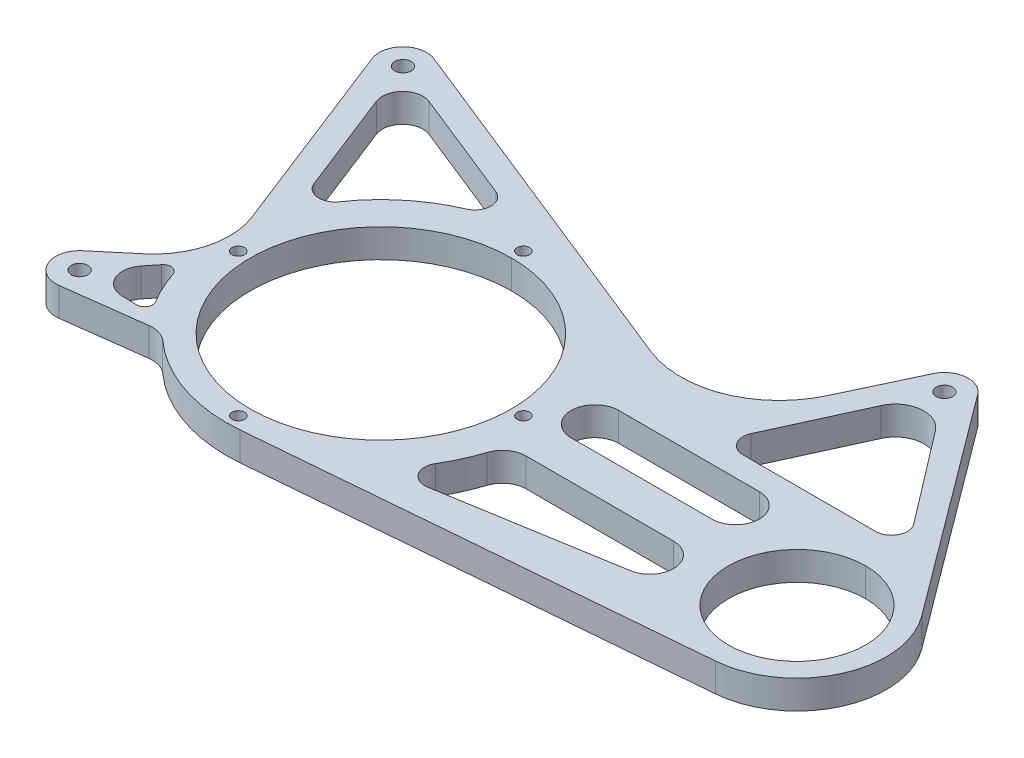
SolidWorks part; units mm, degrees
material "7075-T6 (SN)"
ref_plane "X-Y Datum" through (0, 0, 0) normal (0, 0, 1) x (1, 0, 0)
ref_plane "X-Z Datum" through (0, 0, 0) normal (0, 1, 0) x (1, 0, 0)
ref_plane "Y-Z Datum" through (0, 0, 0) normal (1, 0, 0) x (0, 0, -1)
sketch "Sketch1" plane through (0, 0, 0) normal (0, 1, 0) x (1, 0, 0)
  line L0 (-228.6, -165.1) -> (-123.19, -116.0015) construction
  line L1 (0, 0) -> (54.61, -127) construction
  line L2 (-123.19, -116.0015) -> (54.61, -127) construction
  line L3 (-228.6, -165.1) -> (-228.6, 0) construction
  line L4 (-116.84, 0) -> (0, 0) construction
  line L5 (-228.6, 0) -> (-116.84, 0) construction
  line L10 (-228.6, 0) -> (-123.19, -116.0015) construction
  line L11 (-123.19, -116.0015) -> (10.0337, -23.3342) construction
  line L15 (-207.9749, -9.9568) -> (-62.7807, -68.145)
  line L16 (-117.8957, -177.6872) -> (57.6671, -162.619)
  line L17 (17.67, -17.641) -> (83.2712, -105.6318)
  line L18 (1.4126, -19.2843) -> (-12.1766, -48.2122)
  line L20 (-211.7072, -147.0868) -> (-198.1514, -135.6819)
  line L21 (-220.3888, -22.2676) -> (-189.4301, -101.4224)
  line L22 (-172.4434, -159.7008) -> (-204.3552, -163.8219)
  circle A0 centre (-211.5182, -18.7982) radius 9.525 construction
  circle A2 centre (10.0337, -23.3342) radius 9.525 construction
  circle A3 centre (-211.5182, -18.7982) radius 3.3 construction
  circle A4 centre (-205.5752, -154.3754) radius 3.3 construction
  circle A5 centre (-123.19, -116.0015) radius 52.3875
  circle A6 centre (54.61, -127) radius 27.5
  circle A7 centre (0, 0) radius 12.7 construction
  circle A8 centre (-228.6, -165.1) radius 12.7 construction
  circle A9 centre (-228.6, 0) radius 12.7 construction
  circle A10 centre (10.0337, -23.3342) radius 3.3 construction
  circle A11 centre (-123.19, -173.1515) radius 2.5 construction
  circle A14 centre (-123.19, -116.0015) radius 61.9125 construction
  circle A15 centre (-123.19, -116.0015) radius 57.15 construction
  circle A17 centre (-205.5752, -154.3754) radius 9.525 construction
  circle A18 centre (54.61, -127) radius 35.75 construction
  circle A19 centre (-48.0406, -31.3647) radius 39.624 construction
  arc A20 (-12.1766, -48.2122) -> (-62.7807, -68.145) centre (-48.0406, -31.3647) cw
  arc A24 (57.6671, -162.619) -> (83.2712, -105.6318) centre (54.61, -127) ccw
  arc A25 (1.4126, -19.2843) -> (17.67, -17.641) centre (10.0337, -23.3342) cw
  circle A27 centre (-217.6792, -112.471) radius 30.3329 construction
  arc A29 (-198.1514, -135.6819) -> (-189.4301, -101.4224) centre (-217.6792, -112.471) ccw
  arc A30 (-220.3888, -22.2676) -> (-207.9749, -9.9568) centre (-211.5182, -18.7982) cw
  arc A31 (-164.4265, -162.1827) -> (-117.8957, -177.6872) centre (-123.19, -116.0015) ccw
  circle A32 centre (-171.1504, -169.7128) radius 10.0952 construction
  arc A33 (-204.3552, -163.8219) -> (-211.7072, -147.0868) centre (-205.5752, -154.3754) cw
  arc A34 (-172.4434, -159.7008) -> (-164.4265, -162.1827) centre (-171.1504, -169.7128) cw
  point P36 (-123.19, -116.0015)
  dimension "D1" = 165.1
  dimension "D2" = 105.41
  dimension "D8" = 25.4
  dimension "D9" = 104.775
  dimension "D10" = 55
  dimension "D11" = 19.05
  dimension "D12" = 6.6
  dimension "D23" = 5
  dimension "D14" = 123.825
  dimension "D19" = 79.248
  dimension "D20" = 31.3647
  dimension "D16" = 71.5
  dimension "D25" = 20.1904
  dimension "D21" = 20.9
  dimension "D26" = 60.6657
  dimension "D3" = 111.76
  dimension "D4" = 228.6
  dimension "D5" = 127
  dimension "D6" = 49.0985
  dimension "D7" = 283.21
  dimension "D13" = 25.4
  dimension "D15" = 25.4
  dimension "D17" = 25.4
  dimension "D18" = 48.0406
  dimension "D22" = 34.4248
  dimension "D24" = 57.15
  dimension "D27" = 10.9208
extrude "Boss-Extrude1" add sketch "Sketch1" along normal blind 11.43
hole_wizard "M6 Clearance Hole1" positions "Sketch2" profile "Sketch3" hole size "M6" standard "ANSI Metric" end condition through all
sketch "Sketch2" plane through (0, 0, 0) normal (0, -1, 0) x (-1, 0, 0)
  point P0 (-10.0337, -23.3342)
  point P3 (211.5182, -18.7982)
  point P6 (205.5752, -154.3754)
sketch "Sketch3" plane through (10.0337, 0, 23.3342) normal (1, 0, 0) x (0, 0, -1)
  line L0 (0, 0) -> (0, 11.43)
  line L1 (0, 11.43) -> (3.3, 11.43)
  line L2 (3.3, 11.43) -> (3.3, 0)
  line L5 (3.3, 0) -> (0, 0)
  line L11 (0, -6.35) -> (0, 107.95) construction
  dimension "Thru Hole Dia." = 6.6
  dimension "Thru Hole Depth" = 11.43
hole_wizard "Ø5.0mm Dowel Hole1" positions "Sketch4" profile "Sketch5" hole size "Ø5.0" standard "ANSI Metric" end condition through all
sketch "Sketch4" plane through (0, 0, 0) normal (0, -1, 0) x (-1, 0, 0)
  point P0 (123.19, -173.1515)
sketch "Sketch5" plane through (-123.19, 0, 173.1515) normal (1, 0, 0) x (0, 0, -1)
  line L0 (0, 0) -> (0, 11.43)
  line L1 (0, 11.43) -> (2.5, 11.43)
  line L2 (2.5, 11.43) -> (2.5, 0)
  line L5 (2.5, 0) -> (0, 0)
  line L11 (0, -6.35) -> (0, 107.95) construction
  dimension "Thru Hole Dia." = 5
  dimension "Thru Hole Depth" = 11.43
pattern_circular "CirPattern1" count 4 over 360 about axis through (-123.19, 0, 116.0015) along (0, 1, 0) of "Ø5.0mm Dowel Hole1"
ref_point "Point1"
ref_point "Point2"
ref_plane "Plane1" through (-123.19, 0, 0) normal (1, 0, 0) x (0, 0, -1)
ref_plane "Plane2" through (54.61, 0, 0) normal (1, 0, 0) x (0, 0, -1)
split line "Split Line1"
split line "Split Line2"
sketch "Sketch6" plane through (0, 0, 0) normal (0, -1, 0) x (1, 0, 0)
  line L0 (-14.2347, 76.5807) -> (2.0865, 40.7709)
  line L1 (21.6652, 38.5626) -> (49.7711, 75.3598)
  line L2 (-204.6607, 36.3314) -> (-188.6269, 77.3262)
  line L3 (-194.0427, 25.8017) -> (-149.3861, 43.6983)
  line L5 (-8.4565, 85.5642) -> (44.7247, 85.5642)
  line L8 (-220.3888, 22.2676) -> (-189.4301, 101.4224) construction
  line L9 (17.67, 17.641) -> (83.2712, 105.6318) construction
  line L10 (1.4126, 19.2843) -> (-12.1766, 48.2122) construction
  line L11 (-207.9749, 9.9568) -> (-62.7807, 68.145) construction
  line L15 (-228.6, 165.1) -> (-123.19, 116.0015) construction
  line L17 (-190.9857, 136.0276) -> (-194.6927, 140.6895)
  line L18 (-182.1426, 155.013) -> (-188.0965, 154.851)
  circle A0 centre (10.0337, 23.3342) radius 3.3 construction
  circle A1 centre (10.0337, 23.3342) radius 3.3 construction
  arc A2 (54.61, 99.5) -> (54.61, 154.5) centre (54.61, 127) ccw construction
  circle A3 centre (-8.4565, 79.2142) radius 6.35 construction
  circle A4 centre (44.7247, 79.2142) radius 6.35 construction
  circle A5 centre (12.5377, 45.5343) radius 11.4855 construction
  arc A6 (2.0865, 40.7709) -> (21.6652, 38.5626) centre (12.5377, 45.5343) ccw
  arc A8 (49.7711, 75.3598) -> (44.7247, 85.5642) centre (44.7247, 79.2142) ccw
  arc A9 (-14.2347, 76.5807) -> (-8.4565, 85.5642) centre (-8.4565, 79.2142) cw
  circle A10 centre (-182.5949, 74.967) radius 6.477 construction
  circle A11 centre (-151.7955, 49.7105) radius 6.477 construction
  circle A14 centre (-197.0734, 33.3639) radius 8.1469 construction
  arc A15 (-204.6607, 36.3314) -> (-194.0427, 25.8017) centre (-197.0734, 33.3639) ccw
  arc A25 (-149.3861, 43.6983) -> (-149.2293, 55.6575) centre (-151.7955, 49.7105) ccw
  circle A26 centre (-123.19, 116.0015) radius 65.7225
  circle A27 centre (-123.19, 116.0015) radius 65.7225 construction
  arc A28 (-149.2293, 55.6575) -> (-177.2657, 78.6482) centre (-123.19, 116.0015) cw
  arc A29 (-188.6269, 77.3262) -> (-177.2657, 78.6482) centre (-182.5949, 74.967) cw
  circle A31 centre (-182.0558, 151.8264) radius 3.1877 construction
  circle A32 centre (-188.4906, 138.0115) radius 3.1877 construction
  circle A33 centre (-187.859, 146.1234) radius 8.7308 construction
  arc A34 (-185.4699, 136.9934) -> (-179.3328, 150.1692) centre (-123.19, 116.0015) cw
  arc A35 (-179.3328, 150.1692) -> (-182.1426, 155.013) centre (-182.0558, 151.8264) ccw
  arc A36 (-185.4699, 136.9934) -> (-190.9857, 136.0276) centre (-188.4906, 138.0115) cw
  arc A37 (-194.6927, 140.6895) -> (-188.0965, 154.851) centre (-187.859, 146.1234) cw
  dimension "D3" = 12.7
  dimension "D4" = 22.2001
  dimension "D5" = 12.954
  dimension "D9" = 6.3754
  dimension "D10" = 7.62
  dimension "D1" = 0.667
  dimension "D2" = 0.66
  dimension "D6" = 55.88
  dimension "D7" = 14.4448
  dimension "D8" = 3.81
  dimension "D11" = 7.62
extrude "Cut-Extrude1" cut sketch "Sketch6" against normal through all
sketch "Sketch7" plane through (0, 0, 0) normal (0, -1, 0) x (1, 0, 0)
  line L0 (-48.8157, 114.0965) -> (7.5723, 114.0965)
  line L1 (-48.8157, 95.0465) -> (7.5723, 95.0465)
  line L4 (-60.4801, 159.9806) -> (9.1433, 148.338)
  line L6 (-51.5252, 129.4185) -> (7.5723, 129.4185)
  line L7 (-123.19, 116.0015) -> (54.61, 127) construction
  circle A0 centre (-48.8157, 104.5715) radius 9.525 construction
  circle A3 centre (7.5723, 104.5715) radius 9.525 construction
  arc A4 (-48.8157, 95.0465) -> (-48.8157, 114.0965) centre (-48.8157, 104.5715) cw
  arc A5 (7.5723, 95.0465) -> (7.5723, 114.0965) centre (7.5723, 104.5715) ccw
  circle A12 centre (-51.5252, 138.9435) radius 9.525 construction
  circle A13 centre (7.5723, 138.9435) radius 9.525 construction
  circle A14 centre (-61.5483, 153.5923) radius 6.477 construction
  arc A15 (-60.5967, 136.0394) -> (-67.0782, 150.2201) centre (-123.19, 116.0015) ccw
  arc A16 (-67.0782, 150.2201) -> (-60.4801, 159.9806) centre (-61.5483, 153.5923) cw
  arc A17 (-60.5967, 136.0394) -> (-51.5252, 129.4185) centre (-51.5252, 138.9435) ccw
  arc A18 (7.5723, 129.4185) -> (9.1433, 148.338) centre (7.5723, 138.9435) ccw
  circle A28 centre (-123.19, 116.0015) radius 65.7225
  circle A29 centre (-123.19, 116.0015) radius 65.7225 construction
  dimension "D1" = 19.05
  dimension "D2" = 11.43
  dimension "D5" = 12.954
  dimension "D3" = 14.8249
  dimension "D4" = 56.388
  dimension "D7" = 33.7133
  dimension "D6" = 3.81
extrude "Cut-Extrude2" cut sketch "Sketch7" against normal through all
